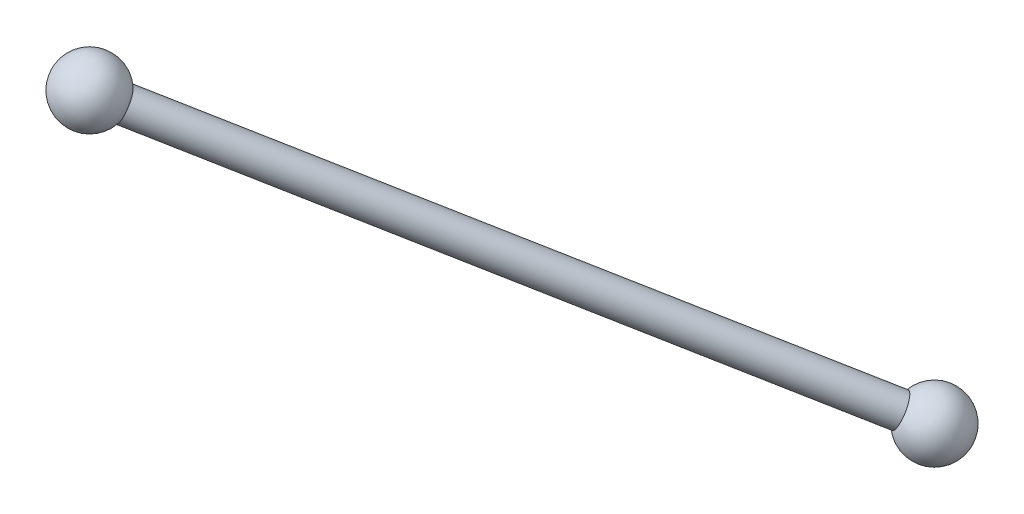
SolidWorks part; units mm, degrees
other "Compression Inner Strut Lane2"
ref_plane "Front Plane" through (0, 0, 0) normal (0, 0, 1) x (1, 0, 0)
ref_plane "Top Plane" through (0, 0, 0) normal (0, 1, 0) x (1, 0, 0)
ref_plane "Right Plane" through (0, 0, 0) normal (1, 0, 0) x (0, 0, -1)
sketch3d "Straight strut core sketch datum points"
  point P0 (-71.2917, -73, 25.9808)
  point P1 (-63.5805, -69.4081, 31.2378)
  point P2 (-71.2917, -81.2568, 31.6222)
ref_plane "Straight strut core sketch plane" through (-19.2131, 13.1273, 19.2131) normal (0.6367, -0.435, -0.6367) x (-0.7711, -0.3592, -0.5257)
sketch "Straight strut core sketch" plane through (-19.2131, 13.1273, 19.2131) normal (0.6367, -0.435, -0.6367) x (-0.7711, -0.3592, -0.5257)
  circle A0 centre (67.5366, -74.9313) radius 1.5
extrude "Straight strut core" add sketch "Straight strut core sketch" along normal blind 64.3649 separate body
sketch3d "Ball end1 axis line"
  line L0 (-71.2917, -73, 15.9808) -> (-71.2917, -73, 35.9808) construction
ref_axis "Ball end1 axis" through (-71.2917, -73, 15.9808) along (0, 0, 1)
sketch3d "Ball end1 profile datum points"
  point P0 (-71.2917, -73, 25.9808)
  point P1 (-61.2917, -73, 25.9808)
  point P2 (-71.2917, -73, 35.9808)
ref_plane "Ball end1 profile plane" through (0, -73, 0) normal (0, -1, 0) x (-1, 0, 0)
sketch "Ball end1 profile" plane through (0, -73, 0) normal (0, -1, 0) x (-1, 0, 0)
  line L0 (71.2917, -28.9808) -> (71.2917, -22.9808)
  arc A0 (71.2917, -22.9808) -> (71.2917, -28.9808) centre (71.2917, -25.9808) ccw
revolve "Ball end1" add sketch "Ball end1 profile" angle 360 about axis through (-71.2917, -73, 15.9808) along (0, 0, 1)
sketch3d "Ball end2 axis line"
  line L0 (-30.3109, -101, -25) -> (-30.3109, -101, -5) construction
ref_axis "Ball end2 axis" through (-30.3109, -101, -25) along (0, 0, 1)
sketch3d "Ball end2 profile datum points"
  point P0 (-30.3109, -101, -15)
  point P1 (-20.3109, -101, -15)
  point P2 (-30.3109, -101, -5)
ref_plane "Ball end2 profile plane" through (0, -101, 0) normal (0, -1, 0) x (-1, 0, 0)
sketch "Ball end2 profile" plane through (0, -101, 0) normal (0, -1, 0) x (-1, 0, 0)
  line L0 (30.3109, 12) -> (30.3109, 18)
  arc A0 (30.3109, 18) -> (30.3109, 12) centre (30.3109, 15) ccw
revolve "Ball end2" add sketch "Ball end2 profile" angle 360 about axis through (-30.3109, -101, -25) along (0, 0, 1)
